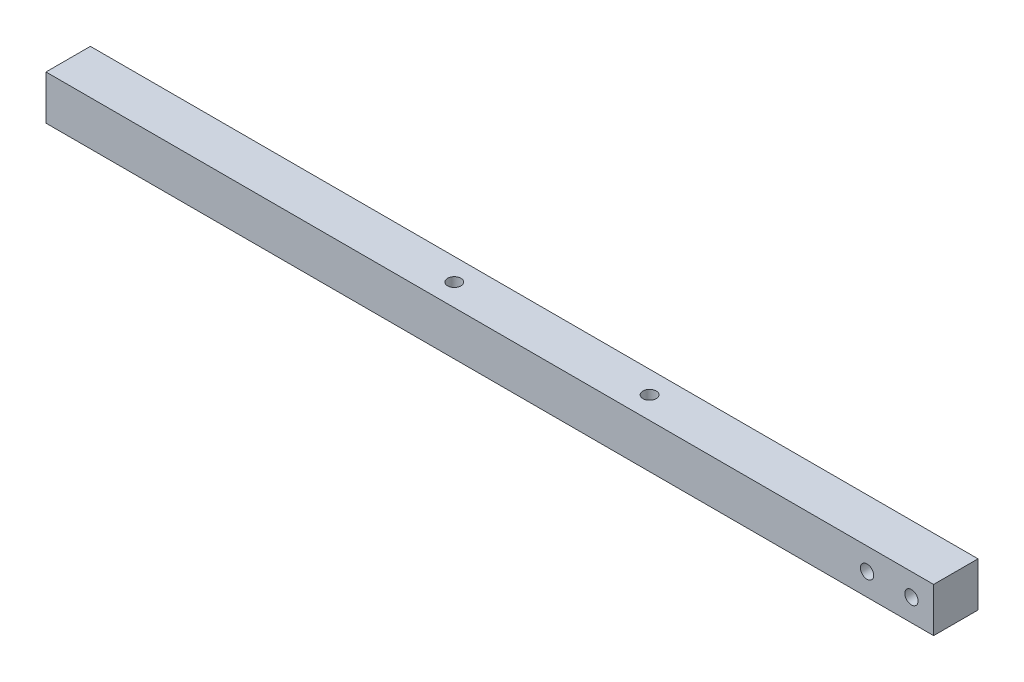
SolidWorks part; units mm, degrees
ref_plane "Front" through (0, 0, 0) normal (0, 0, 1) x (1, 0, 0)
ref_plane "Top" through (0, 0, 0) normal (0, 1, 0) x (1, 0, 0)
ref_plane "Right" through (0, 0, 0) normal (1, 0, 0) x (0, 0, -1)
sketch "Skizze1" plane through (0, 0, 0) normal (1, 0, 0) x (0, 0, -1)
  line L1 (-10, -10) -> (10, -10)
  line L2 (-10, -10) -> (-10, 10)
  line L3 (-10, 10) -> (10, 10)
  line L4 (10, -10) -> (10, 10)
  line L5 (-10, -10) -> (10, 10) construction
  line L6 (-10, 10) -> (10, -10) construction
  point P0 (0, 0)
  dimension "D1" = 20
extrude "Aufsatz-Linear austragen1" add sketch "Skizze1" along normal blind 400
sketch "Skizze2" plane through (0, 10, 0) normal (0, 1, 0) x (1, 0, 0)
  line L0 (0, 0) -> (400, 0) construction
  line L1 (0, 10) -> (0, -10) construction
  line L2 (400, 10) -> (400, -10) construction
  line L3 (200, 0) -> (200, 10) construction
  line L4 (400, 10) -> (0, 10) construction
  circle A0 centre (174, 0) radius 3
  circle A2 centre (262, 0) radius 3
  circle A3 centre (202, 0) radius 3 construction
  dimension "D2" = 6
  dimension "D1" = 174
  dimension "D3" = 262
  dimension "D4" = 202
extrude "Schnitt-Linear austragen1" cut sketch "Skizze2" against normal through all
sketch "Sketch1" plane through (0, 0, 10) normal (0, 0, 1) x (1, 0, 0)
  line L0 (0, 0) -> (400, 0) construction
  line L1 (400, 10) -> (400, -10) construction
  circle A0 centre (390, 0) radius 3
  circle A1 centre (370, 0) radius 3
  dimension "D1" = 6
  dimension "D2" = 10
  dimension "D3" = 20
extrude "Extrude1" cut sketch "Sketch1" against normal through all
